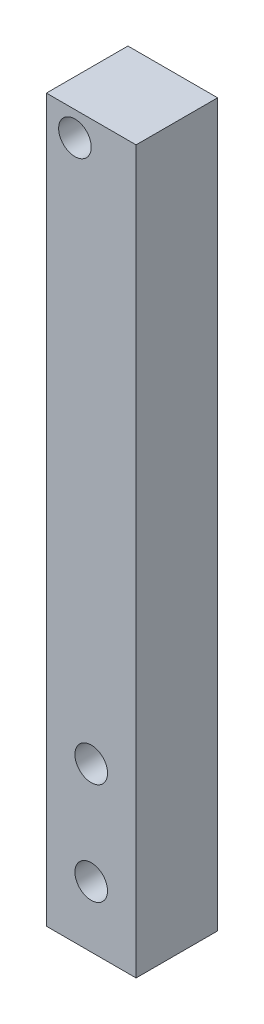
SolidWorks part; units mm, degrees
ref_plane "前视基准面" through (0, 0, 0) normal (0, 0, 1) x (1, 0, 0)
ref_plane "上视基准面" through (0, 0, 0) normal (0, 1, 0) x (1, 0, 0)
ref_plane "右视基准面" through (0, 0, 0) normal (1, 0, 0) x (0, 0, -1)
sketch "草图4" plane through (0, 0, 0) normal (0, 0, 1) x (1, 0, 0)
  line L0 (0, 0) -> (15, 0) construction
  line L1 (-7, 6) -> (15, 6)
  line L2 (-7, 6) -> (-7, -6)
  line L3 (-7, -171) -> (15, -171)
  line L4 (15, 6) -> (15, -6)
  line L5 (15, -6) -> (-7, -6) construction
  line L6 (15, -6) -> (15, -171)
  line L8 (-7, -6) -> (-7, -171)
  circle A0 centre (0, 0) radius 4
  dimension "D4" = 8
  dimension "D1" = 12
  dimension "D2" = 22
  dimension "D3" = 15
  dimension "D5" = 165
extrude "凸台-拉伸3" add sketch "草图4" along normal blind 20
sketch "草图5" plane through (0, 0, 20) normal (0, 0, 1) x (1, 0, 0)
  line L0 (4, -171) -> (4, -156) construction
  line L1 (-7, -171) -> (15, -171) construction
  line L2 (4, -156) -> (4, -131) construction
  circle A0 centre (4, -131) radius 4
  circle A1 centre (4, -156) radius 4
  dimension "D1" = 8
  dimension "D2" = 8
  dimension "D3" = 25
  dimension "D4" = 15
extrude "切除-拉伸1" cut sketch "草图5" against normal up to next
